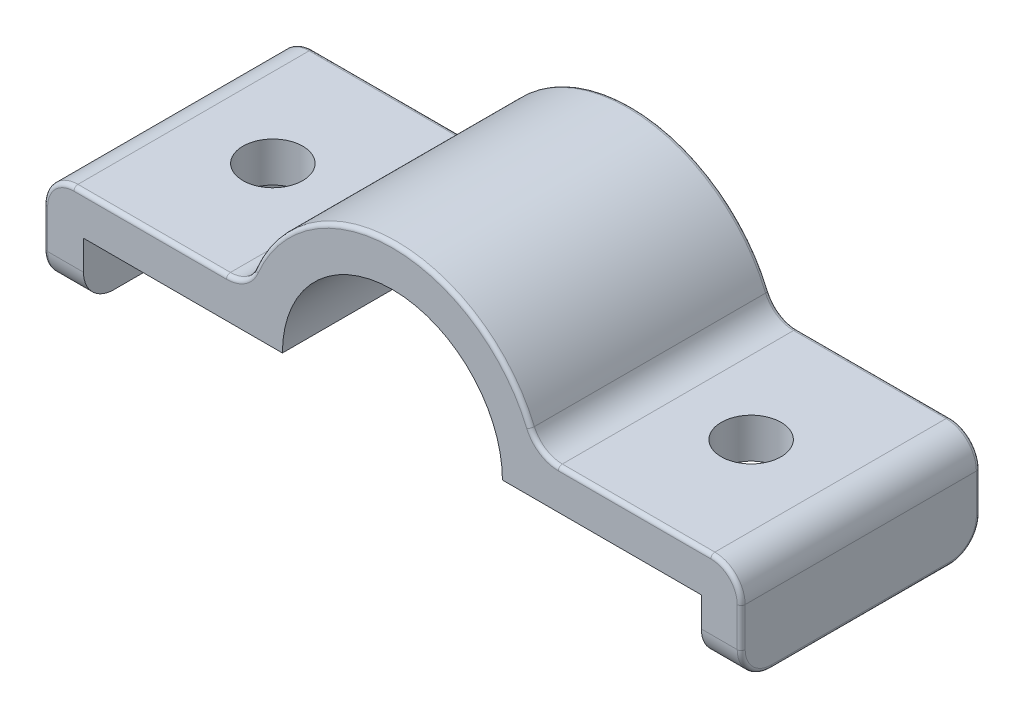
SolidWorks part; units mm, degrees
ref_plane "Front Plane" through (0, 0, 0) normal (0, 0, 1) x (1, 0, 0)
ref_plane "Top Plane" through (0, 0, 0) normal (0, 1, 0) x (1, 0, 0)
ref_plane "Right Plane" through (0, 0, 0) normal (1, 0, 0) x (0, 0, -1)
sketch "Sketch1" plane through (0, 0, 0) normal (0, 0, 1) x (1, 0, 0)
  line L0 (-182.0443, 0) -> (182.0443, 0) construction
  line L1 (-35.052, 0) -> (-98.425, 0)
  line L2 (-98.425, 0) -> (-98.425, -19.05)
  line L3 (-98.425, -19.05) -> (-111.125, -19.05)
  line L4 (-111.125, -19.05) -> (-111.125, 12.7)
  line L5 (-111.125, 12.7) -> (-46.0322, 12.7)
  line L6 (35.052, 0) -> (98.425, 0)
  line L7 (98.425, 0) -> (98.425, -19.05)
  line L8 (98.425, -19.05) -> (111.125, -19.05)
  line L9 (111.125, -19.05) -> (111.125, 12.7)
  line L10 (111.125, 12.7) -> (46.0322, 12.7)
  line L11 (0, 0) -> (0, 79.6116) construction
  arc A0 (35.052, 0) -> (-35.052, 0) centre (0, 0) ccw
  arc A1 (46.0322, 12.7) -> (-46.0322, 12.7) centre (0, 0) ccw
  point P1 (0, 0)
  dimension "D1" = 70.104
  dimension "D2" = 12.7
  dimension "D3" = 12.7
  dimension "D4" = 12.7
  dimension "D5" = 222.25
  dimension "D6" = 31.75
extrude "Boss-Extrude1" add sketch "Sketch1" along normal mid plane 76.2
sketch "Sketch3" plane through (0, 12.7, 0) normal (0, 1, 0) x (1, 0, 0)
  line L0 (0, 38.1) -> (0, -38.1) construction
  line L1 (46.0322, 38.1) -> (-46.0322, 38.1) construction
  line L2 (-46.0322, -38.1) -> (46.0322, -38.1) construction
  circle A0 centre (-76.2, 0) radius 9.525
  circle A1 centre (76.2, 0) radius 9.525
  point P11 (0, 0)
  dimension "D2" = 19.05
  dimension "D1" = 152.4
extrude "Cut-Extrude1" cut sketch "Sketch3" against normal through all
fillet "Fillet1" radius 9.652 8 edges at (104.775, -19.05, -38.1) (-104.775, -19.05, -38.1) (-46.0322, 12.7, 0) (-111.125, 12.7, 0) (111.125, 12.7, 0) (46.0322, 12.7, 0) (-104.775, -19.05, 38.1) (104.775, -19.05, 38.1)
fillet "Fillet2" radius 1.27 24 edges at (47.5403, 14.3072, -38.1) (77.1733, 12.7, -38.1) (108.298, 9.873, -38.1) (111.125, -3.175, -38.1) (111.125, -16.223, -35.273) (111.125, -19.05, 0) (111.125, -16.223, 35.273) (111.125, -3.175, 38.1) (108.298, 9.873, 38.1) (77.1733, 12.7, 38.1) (47.5403, 14.3072, 38.1) (0, 47.752, 38.1) (-47.5403, 14.3072, 38.1) (-77.1733, 12.7, 38.1) (-108.298, 9.873, 38.1) (-111.125, -3.175, 38.1) (-111.125, -16.223, 35.273) (-111.125, -19.05, 0) (-111.125, -16.223, -35.273) (-111.125, -3.175, -38.1) (-108.298, 9.873, -38.1) (-77.1733, 12.7, -38.1) (-47.5403, 14.3072, -38.1) (0, 47.752, -38.1)
